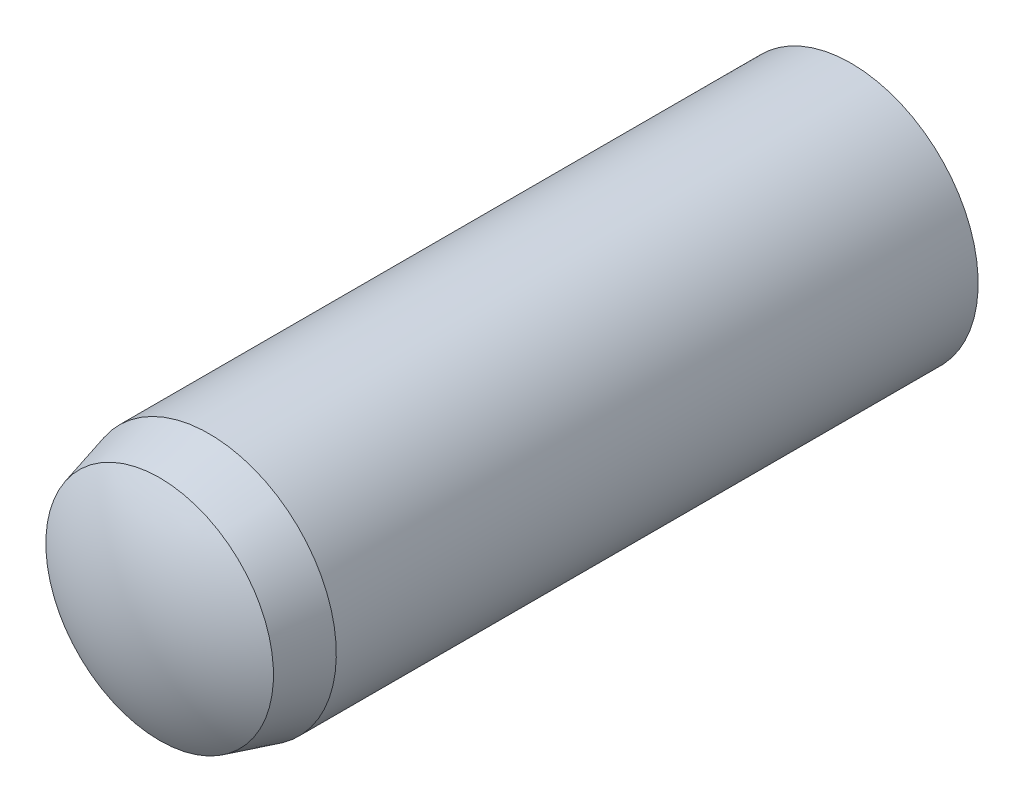
SolidWorks part; units mm, degrees
ref_plane "Front Plane" through (0, 0, 0) normal (0, 0, 1) x (1, 0, 0)
ref_plane "Top Plane" through (0, 0, 0) normal (0, 1, 0) x (1, 0, 0)
ref_plane "Right Plane" through (0, 0, 0) normal (1, 0, 0) x (0, 0, -1)
sketch "Sketch1" plane through (0, 0, 0) normal (0, 0, 1) x (1, 0, 0)
  circle A0 centre (0, 0) radius 4
  point P3 (0, 4)
  dimension "Diameter" = 8
sketch "Sketch2" plane through (0, 0, 0) normal (1, 0, 0) x (0, 0, -1)
  line L0 (-12, 0) -> (12, 0) construction
  line L1 (-12, 0) -> (-12, 4) construction
  line L2 (-12, 4) -> (12, 4)
  line L3 (12, 4) -> (12, 0) construction
  line L4 (-10.96, 3.582) -> (-9.4, 4)
  arc A0 (-12, 0) -> (-10.96, 3.582) centre (-5.3114, 0) cw
  arc A1 (12, 0) -> (10.8, 4) centre (4.7333, 0) ccw
  point P2 (0, 0)
  point P11 (-4, 0)
  point P13 (4, 0)
  dimension "Length" = 24
  dimension "D1" = 15
  dimension "D2" = 1.2
  dimension "D3" = 2.6
  dimension "D4" = 1.56
  dimension "D5" = 8
  dimension "D6" = 8
sketch "Sketch3" plane through (0, 0, 0) normal (1, 0, 0) x (0, 0, -1)
  line L0 (-12, 0) -> (12, 0) construction
  line L1 (-10.96, 3.582) -> (-9.4, 4) construction
  line L2 (-12, 0) -> (12, 0)
  line L3 (-10.96, 3.582) -> (-9.4, 4)
  line L4 (-9.4, 4) -> (10.8, 4)
  arc A0 (12, 0) -> (10.8, 4) centre (4.7333, 0) ccw construction
  arc A1 (-10.96, 3.582) -> (-12, 0) centre (-5.3114, 0) ccw construction
  arc A2 (12, 0) -> (10.8, 4) centre (4.7333, 0) ccw
  arc A3 (-10.96, 3.582) -> (-12, 0) centre (-5.3114, 0) ccw
revolve "Revolve1" add sketch "Sketch3" angle 360 about L2
equation "\"D2@Sketch2\" = \"Diameter@Sketch1\" * .15"
equation "\"D3@Sketch2\" = \"Diameter@Sketch1\" * .325"
equation "\"D4@Sketch2\" = \"D3@Sketch2\" * .6"
equation "\"D5@Sketch2\"=\"Diameter@Sketch1\""
equation "\"D6@Sketch2\"=\"D5@sketch2\""
